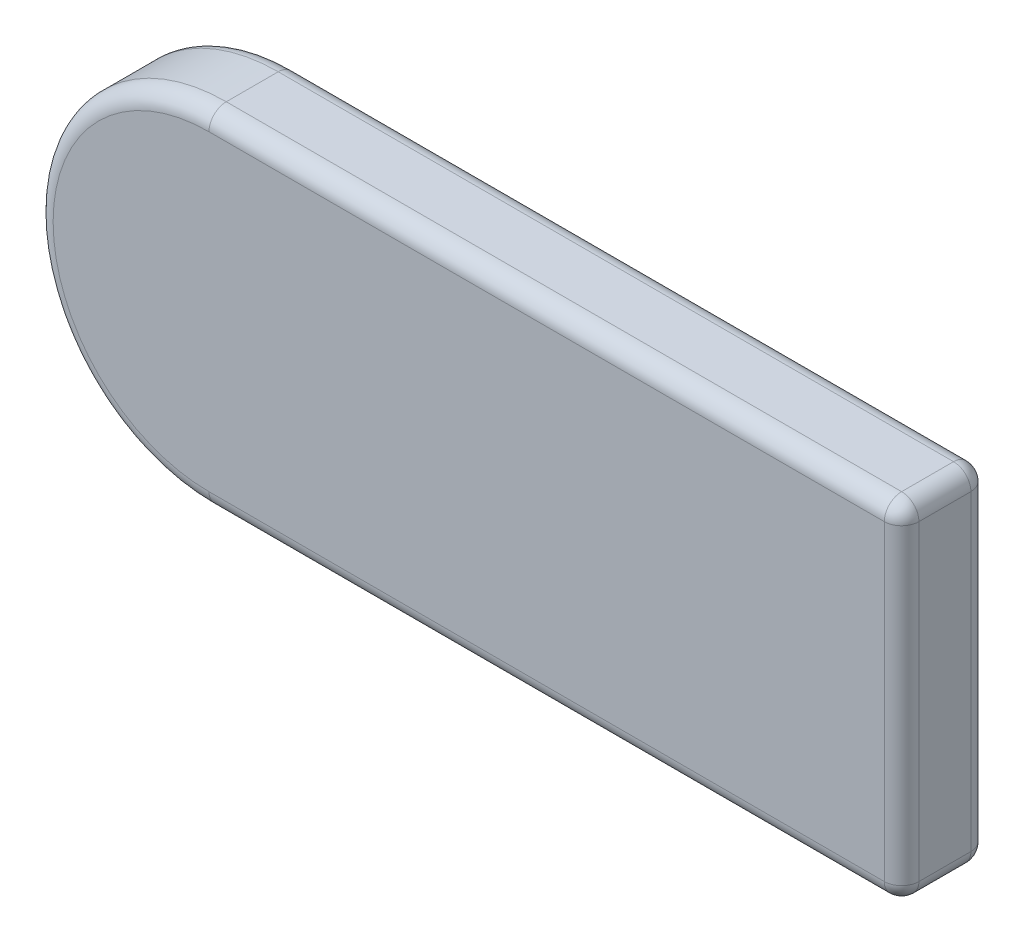
SolidWorks part; units mm, degrees
ref_plane "Front Plane" through (0, 0, 0) normal (0, 0, 1) x (1, 0, 0)
ref_plane "Top Plane" through (0, 0, 0) normal (0, 1, 0) x (1, 0, 0)
ref_plane "Right Plane" through (0, 0, 0) normal (1, 0, 0) x (0, 0, -1)
sketch "Эскиз1" plane through (0, 0, 0) normal (0, 0, 1) x (1, 0, 0)
  line L9 (0, 0) -> (-3, 0) construction
  line L10 (2, -1) -> (-2, -1)
  line L11 (2, -1) -> (2, 1)
  line L12 (2, 1) -> (-2, 1)
  line L14 (2, -1) -> (-2, 1) construction
  line L20 (2, 1) -> (-2, -1) construction
  arc A1 (-2, 1) -> (-2, -1) centre (-2, 0) ccw
  point P0 (0, 0)
  dimension "D1" = 4
  dimension "D2" = 2
  dimension "D3" = 3
extrude "Бобышка-Вытянуть1" add sketch "Эскиз1" along normal blind 0.5 contours L12 A1 L10 L11
fillet "Скругление2" radius 0.1 2 edges at (2, -1, 0.25) (2, 1, 0.25)
fillet "Скругление1" radius 0.1 12 edges at (-0.05, 1, 0) (-3, 0, 0) (-0.05, -1, 0) (2, 0, 0) (-0.05, -1, 0.5) (-3, 0, 0.5) (-0.05, 1, 0.5) (2, 0, 0.5) (1.9707, 0.9707, 0) (1.9707, -0.9707, 0) (1.9707, 0.9707, 0.5) (1.9707, -0.9707, 0.5)
